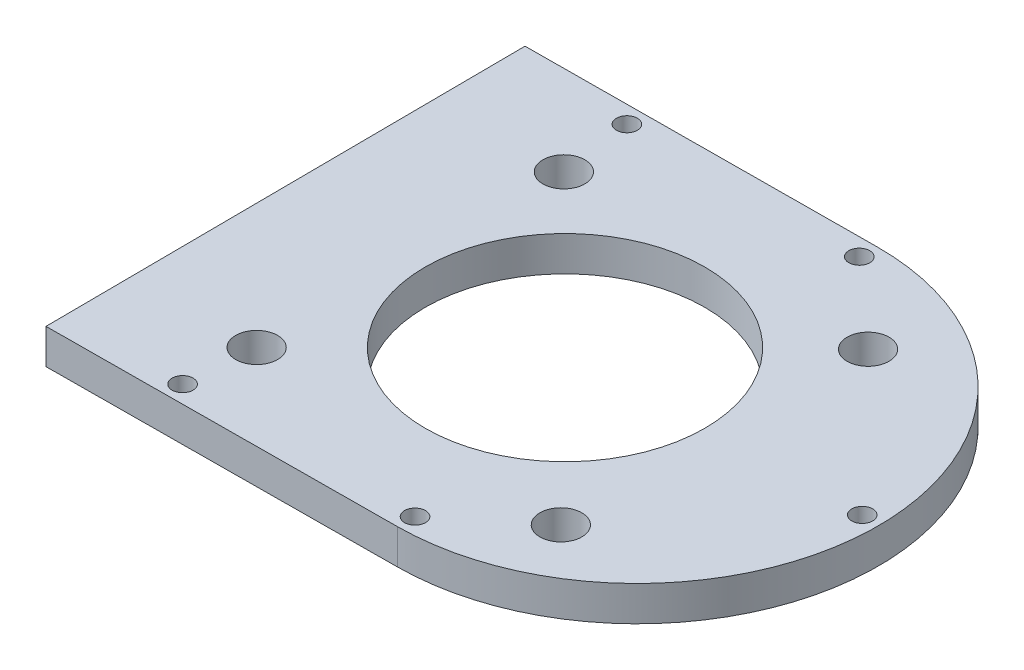
SolidWorks part; units mm, degrees
ref_plane "Front Plane" through (0, 0, 0) normal (0, 0, 1) x (1, 0, 0)
ref_plane "Top Plane" through (0, 0, 0) normal (0, 1, 0) x (1, 0, 0)
ref_plane "Right Plane" through (0, 0, 0) normal (1, 0, 0) x (0, 0, -1)
sketch "Sketch1" plane through (0, 0, 0) normal (0, 1, 0) x (1, 0, 0)
  line L16 (204.265, -121.1651) -> (154.2661, -121.4902) construction
  line L17 (154.2661, -121.4902) -> (154.7148, -190.4888) construction
  line L18 (154.7148, -190.4888) -> (204.7137, -190.1636) construction
  line L31 (204.265, -121.1651) -> (154.2661, -121.4902)
  line L32 (154.2661, -121.4902) -> (154.7148, -190.4888)
  line L33 (154.7148, -190.4888) -> (204.7137, -190.1636)
  line L34 (204.6812, -185.1637) -> (159.6821, -185.4564) construction
  line L35 (159.2985, -126.4576) -> (204.2975, -126.165) construction
  line L36 (159.6821, -185.4564) -> (159.2985, -126.4576) construction
  line L37 (204.6812, -185.1637) -> (159.6821, -185.4564)
  line L38 (159.2985, -126.4576) -> (204.2975, -126.165)
  line L39 (159.6821, -185.4564) -> (159.2985, -126.4576)
  circle A0 centre (194.49, -155.9902) radius 20 construction
  circle A1 centre (194.49, -155.9902) radius 20
  arc A12 (204.7137, -190.1636) -> (204.265, -121.1651) centre (204.4894, -155.6643) ccw construction
  circle A14 centre (216.3715, -134.502) radius 3 construction
  arc A27 (204.7137, -190.1636) -> (204.265, -121.1651) centre (204.4894, -155.6643) ccw
  circle A29 centre (216.3715, -134.502) radius 3
  circle A30 centre (171.232, -123.8799) radius 1.5 construction
  circle A31 centre (204.2813, -123.665) radius 1.5 construction
  circle A32 centre (236.4887, -155.4563) radius 1.5 construction
  circle A33 centre (171.6481, -187.8786) radius 1.5 construction
  circle A34 centre (204.6975, -187.6637) radius 1.5 construction
  arc A35 (204.6812, -185.1637) -> (204.2975, -126.165) centre (204.4894, -155.6643) ccw construction
  circle A36 centre (171.232, -123.8799) radius 1.5
  circle A37 centre (204.2813, -123.665) radius 1.5
  circle A38 centre (236.4887, -155.4563) radius 1.5
  circle A39 centre (171.6481, -187.8786) radius 1.5
  circle A40 centre (204.6975, -187.6637) radius 1.5
  arc A41 (204.6812, -185.1637) -> (204.2975, -126.165) centre (204.4894, -155.6643) ccw
  circle A42 centre (216.1559, -178.2522) radius 3 construction
  circle A43 centre (172.4057, -178.0366) radius 3 construction
  circle A44 centre (172.6213, -134.2864) radius 3 construction
  circle A45 centre (216.1559, -178.2522) radius 3
  circle A46 centre (172.4057, -178.0366) radius 3
  circle A47 centre (172.6213, -134.2864) radius 3
  point P0 (0, 0)
extrude "Boss-Extrude1" add sketch "Sketch1" along normal blind 5
